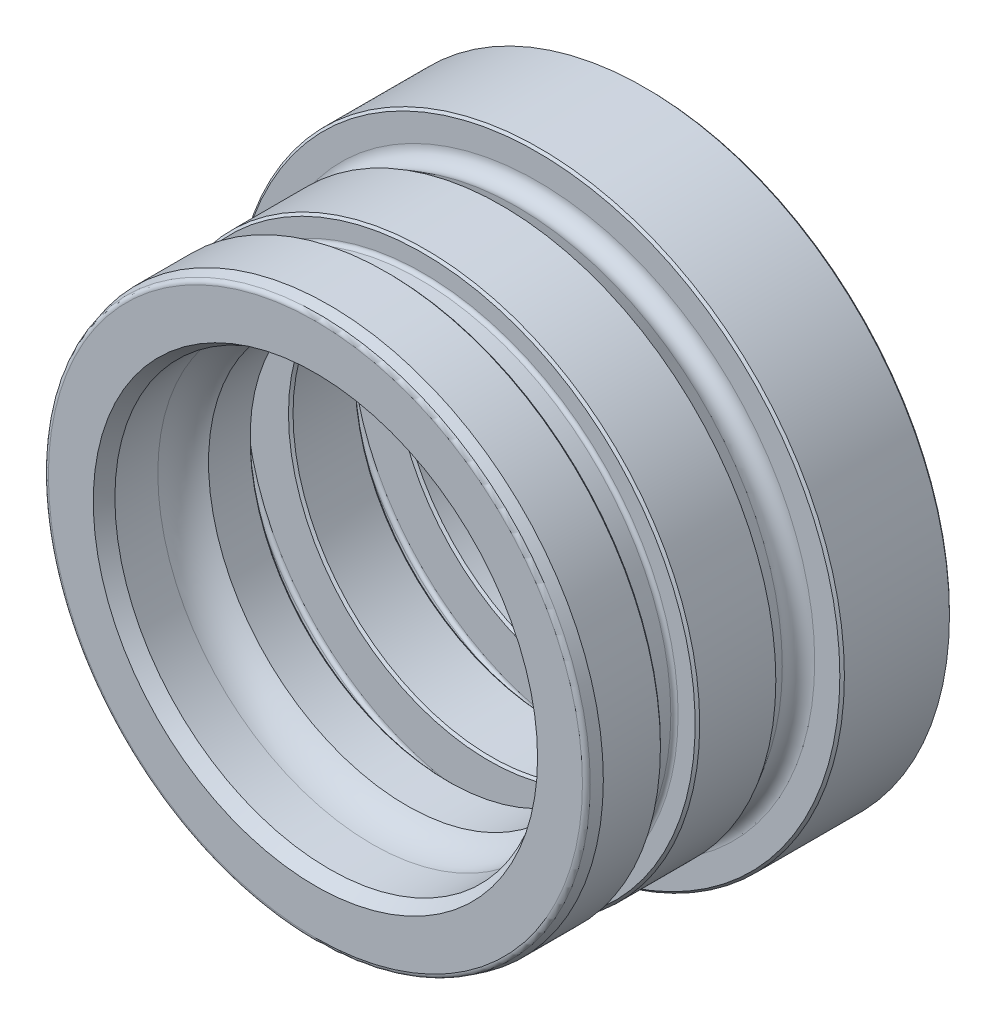
SolidWorks part; units mm, degrees
material "17CrNiMo6"
ref_plane "Front Plane" through (0, 0, 0) normal (0, 0, 1) x (1, 0, 0)
ref_plane "Top Plane" through (0, 0, 0) normal (0, 1, 0) x (1, 0, 0)
ref_plane "Right Plane" through (0, 0, 0) normal (1, 0, 0) x (0, 0, -1)
sketch "Sketch1" plane through (0, 0, 0) normal (1, 0, 0) x (0, 0, -1)
  line L0 (-32.951, 0) -> (165.3793, 0) construction
  line L1 (0, 29.2294) -> (0, 24.316)
  line L3 (1.5, 23.45) -> (6.2003, 23.45)
  line L4 (1.5, 30.015) -> (0.3706, 29.7124)
  line L5 (10, 21.7) -> (14.8, 21.7)
  line L6 (14.8, 21.7) -> (14.8, 26.6)
  line L7 (15.2, 27) -> (18.6, 27)
  line L8 (19, 26.6) -> (19, 21.7)
  line L9 (19, 21.7) -> (26.3, 21.7)
  line L10 (26.3, 21.7) -> (26.3, 26.6)
  line L11 (26.7, 27) -> (30.1, 27)
  line L12 (30.5, 26.6) -> (30.5, 21.7)
  line L13 (30.5, 21.7) -> (35.8, 21.7)
  line L14 (36.3, 33.1) -> (36.05, 33.35)
  line L15 (36.3, 22.2) -> (36.3, 33.1)
  line L16 (36.05, 33.35) -> (24.3, 33.35)
  line L17 (24.3, 33.35) -> (24.3, 30.35)
  line L18 (35.8, 21.7) -> (36.3, 22.2)
  line L19 (22.05, 29.051) -> (20.3802, 30.015)
  line L20 (20.3802, 30.015) -> (11.8, 30.015)
  line L21 (11.8, 30.015) -> (11.8, 27.9)
  line L22 (11.4, 27.5) -> (8.4, 27.5)
  line L23 (8, 27.9) -> (8, 30.015)
  line L24 (8, 30.015) -> (1.5, 30.015)
  line L25 (0, 24.316) -> (1.5, 23.45)
  arc A0 (22.05, 29.051) -> (24.3, 30.35) centre (22.8, 30.35) ccw
  arc A1 (10, 21.7) -> (6.2003, 23.45) centre (6.2003, 18.45) ccw
  arc A2 (8.4, 27.5) -> (8, 27.9) centre (8.4, 27.9) cw
  arc A3 (11.8, 27.9) -> (11.4, 27.5) centre (11.4, 27.9) cw
  arc A4 (15.2, 27) -> (14.8, 26.6) centre (15.2, 26.6) ccw
  arc A5 (19, 26.6) -> (18.6, 27) centre (18.6, 26.6) ccw
  arc A6 (26.7, 27) -> (26.3, 26.6) centre (26.7, 26.6) ccw
  arc A7 (30.5, 26.6) -> (30.1, 27) centre (30.1, 26.6) ccw
  arc A8 (0.3706, 29.7124) -> (0, 29.2294) centre (0.5, 29.2294) ccw
  point P3 (0, 30.015)
  point P4 (0, 23.45)
  point P16 (36.3, 21.7)
  point P18 (36.3, 33.35)
  point P37 (8, 27.5)
  point P40 (11.8, 27.5)
  point P43 (14.8, 27)
  point P46 (19, 27)
  point P49 (26.3, 27)
  point P52 (30.5, 27)
  dimension "D9" = 1.5
  dimension "D8" = 57.7
  dimension "D18" = 10
  dimension "D27" = 0.4
  dimension "D28" = 5
  dimension "D29" = 0.5
  dimension "D1" = 36.3
  dimension "D2" = 46.9
  dimension "D3" = 43.4
  dimension "D4" = 54
  dimension "D5" = 66.7
  dimension "D6" = 60.03
  dimension "D7" = 30
  dimension "D10" = 4.2
  dimension "D11" = 19
  dimension "D12" = 11.8
  dimension "D13" = 3.8
  dimension "D14" = 55
  dimension "D15" = 30.5
  dimension "D16" = 4.2
  dimension "D17" = 12
  dimension "D19" = 1.5
  dimension "D20" = 15
  dimension "D21" = 0.25
  dimension "D22" = 45
  dimension "D23" = 0.5
  dimension "D24" = 45
  dimension "D25" = 1.5
  dimension "D26" = 30
revolve "Revolve1" add sketch "Sketch1" angle 360 about L0
chamfer "Chamfer1" distance 0.25 angle 45 7 edges at (33.35, 0, -24.3) (30.015, 0, -8) (30.015, 0, -11.8) (21.7, 0, -19) (21.7, 0, -14.8) (21.7, 0, -26.3) (21.7, 0, -30.5)
sketch "Sketch2" plane through (0, 0, 0) normal (0, 1, 0) x (1, 0, 0)
  line L1 (22.2, 36.3) -> (-22.2, 36.3) construction
  circle A0 centre (0, 42.8) radius 8
  dimension "D1" = 16
  dimension "D2" = 1.5
extrude "Cut-Extrude1" [suppressed] cut sketch "Sketch2" against normal through all and the other way through all
sketch "Sketch3" plane through (0, 0, 0) normal (1, 0, 0) x (0, 0, -1)
  line L0 (36.3, -33.1) -> (36.3, 33.1) construction
  circle A0 centre (42.8, 0) radius 8
  dimension "D1" = 16
  dimension "D2" = 1.5
extrude "Cut-Extrude2" [suppressed] cut sketch "Sketch3" against normal through all and the other way through all
sketch "Sketch4" plane through (0, 0, 0) normal (0, 1, 0) x (1, 0, 0)
  line L0 (-30.8368, 28.2739) -> (31.9797, 28.2739) construction
  text T0 "7372 2977 01 - F   11111 - XX" font "Century Gothic" height 3
wrap "Wrap1" [suppressed] sketch "Sketch4" source sketch "Sketch4" thickness 0.01 parameters "D1"=0.01
